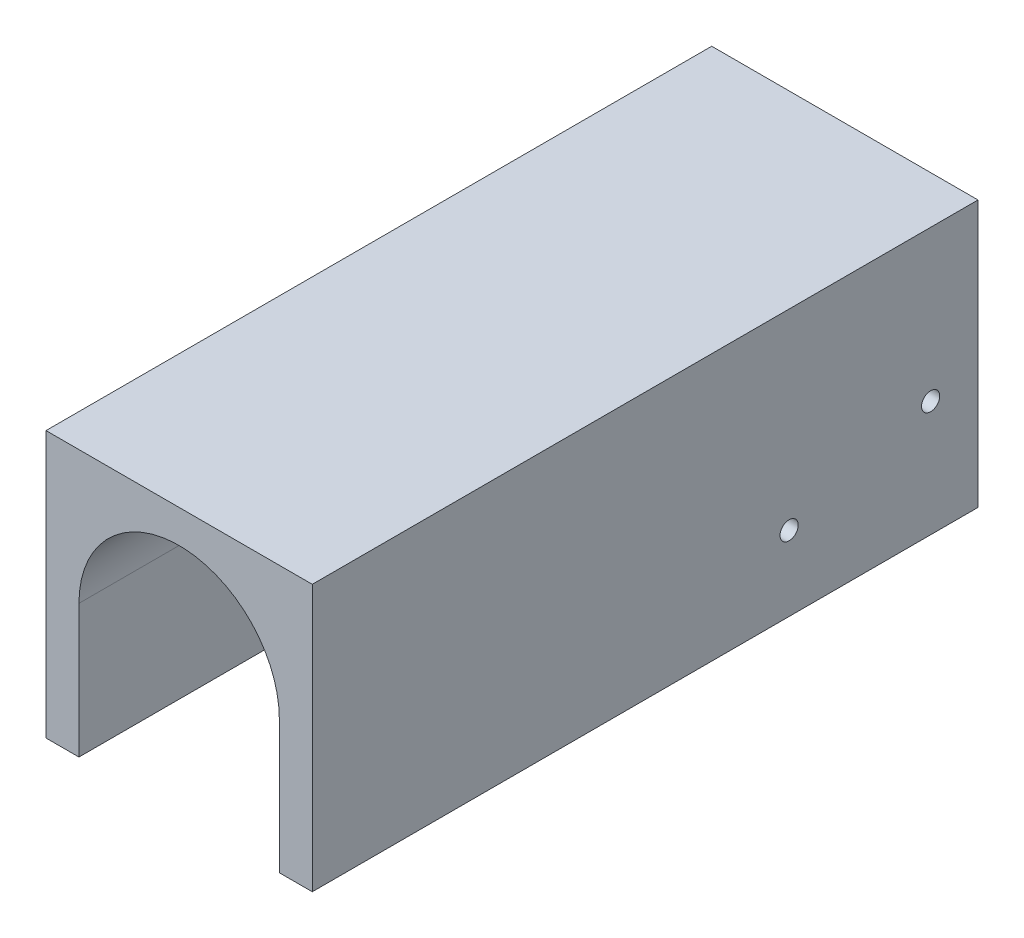
SolidWorks part; units mm, degrees
ref_plane "정면" through (0, 0, 0) normal (0, 0, 1) x (1, 0, 0)
ref_plane "윗면" through (0, 0, 0) normal (0, 1, 0) x (1, 0, 0)
ref_plane "우측면" through (0, 0, 0) normal (1, 0, 0) x (0, 0, -1)
sketch "스케치1" plane through (0, 0, 0) normal (1, 0, 0) x (0, 0, -1)
  line L1 (0, 0) -> (150, 0)
  line L2 (0, 0) -> (0, -60)
  line L3 (0, -60) -> (150, -60)
  line L4 (150, 0) -> (150, -60)
  dimension "D1" = 60
  dimension "D2" = 150
extrude "보스-돌출1" add sketch "스케치1" along normal mid plane 60
sketch "스케치4" plane through (0, 0, 0) normal (0, 0, 1) x (1, 0, 0)
  line L0 (-22.575, -30) -> (-22.575, -60)
  line L1 (30, -60) -> (-30, -60) construction
  line L2 (-22.575, -60) -> (22.575, -60)
  line L3 (22.575, -60) -> (22.575, -30)
  line L4 (0, 0) -> (0, -30) construction
  arc A0 (22.575, -30) -> (-22.575, -30) centre (0, -30) ccw
  dimension "D1" = 22.575
  dimension "D2" = 30
extrude "컷-돌출1" cut sketch "스케치4" against normal blind 100
sketch "스케치5" plane through (0, 0, 0) normal (1, 0, 0) x (0, 0, -1)
  circle A0 centre (107.4464, -43.1748) radius 2.05
  circle A1 centre (139.3314, -33.9391) radius 2.05
  dimension "D1" = 4.1
  dimension "D2" = 4.1
extrude "컷-돌출2" cut sketch "스케치5" against normal through all both and the other way through all
